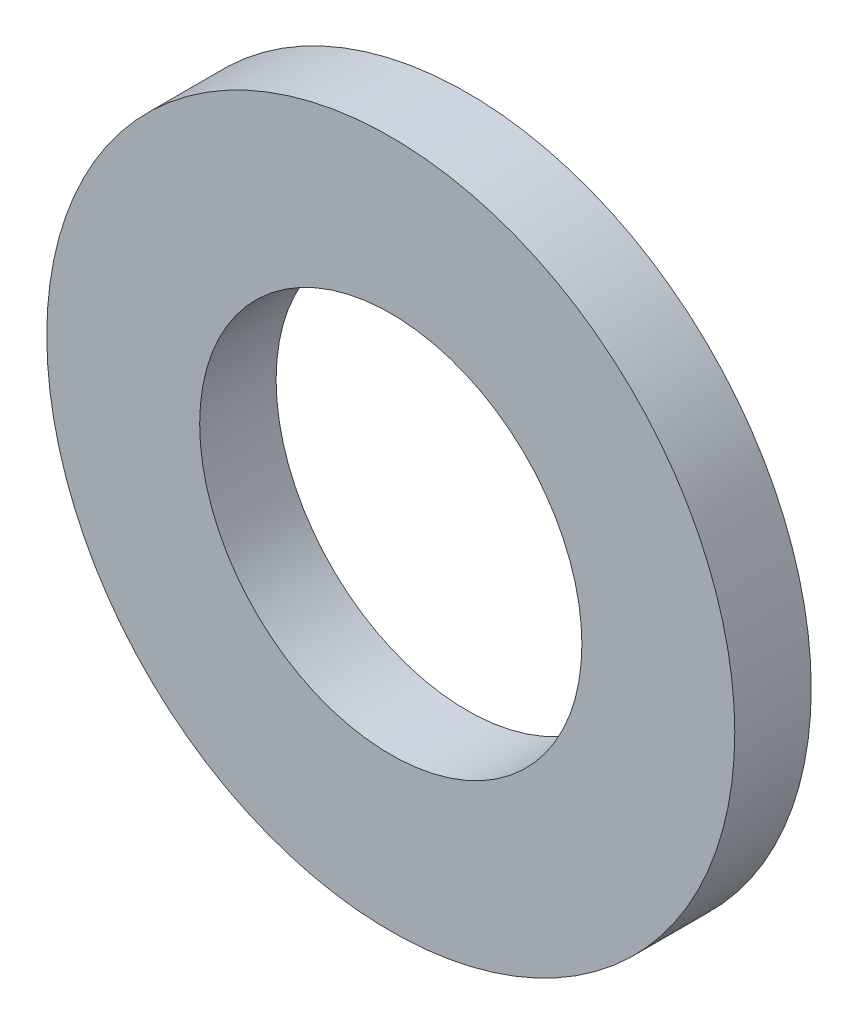
SolidWorks part; units mm, degrees
ref_plane "前视基准面" through (0, 0, 0) normal (0, 0, 1) x (1, 0, 0)
ref_plane "上视基准面" through (0, 0, 0) normal (0, 1, 0) x (1, 0, 0)
ref_plane "右视基准面" through (0, 0, 0) normal (1, 0, 0) x (0, 0, -1)
sketch "草图1" plane through (0, 0, 0) normal (0, 0, 1) x (1, 0, 0)
  circle A0 centre (0, 0) radius 2.5
  circle A1 centre (0, 0) radius 4.5
  dimension "D1" = 5
  dimension "D2" = 9
extrude "凸台-拉伸1" add sketch "草图1" along normal blind 1
